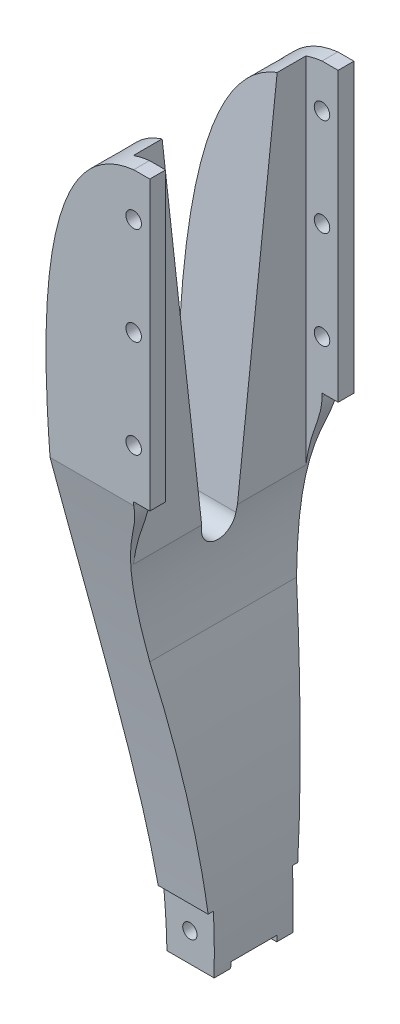
SolidWorks part; units mm, degrees
material "1060-H12"
ref_plane "Front Plane" through (0, 0, 0) normal (0, 0, 1) x (1, 0, 0)
ref_plane "Top Plane" through (0, 0, 0) normal (0, 1, 0) x (1, 0, 0)
ref_plane "Right Plane" through (0, 0, 0) normal (1, 0, 0) x (0, 0, -1)
ref_plane "Plane1" through (0, 35.6, 0) normal (0, 1, 0) x (-1, 0, 0)
sketch "Sketch1" plane through (0, 0, 0) normal (0, 0, 1) x (1, 0, 0)
  line L0 (5.6, 35.6) -> (5.6, -15)
  line L1 (-4.0881, -120.4081) -> (3.5407, -122.8051)
  spline S0 degree 3 poles (5.6, 35.6) (-12.3679, 33.5213) (-8.7824, -50.7826) (5.9542, -91.4515) (-4.0881, -120.4081) knots 0 0 0 0 0.405307 1 1 1 1
  spline S1 degree 2 poles (3.4094, -42.1161) (14.0214, -91.1985) (3.5407, -122.8051) knots 0 0 0 1 1 1
  spline S3 degree 3 poles (5.6, -15) (5.6, -17.2744) (1.6042, -25.848) (2.4158, -35.1136) (3.4094, -42.1161) knots 0 0 0 0 0.227789 0.9215 0.9215 0.9215 0.9215
extrude "Boss-Extrude2" add sketch "Sketch1" along normal blind 35.5
sketch "Sketch3" plane through (0, 0, 0) normal (1, 0, 0) x (0, 0, -1)
  line L0 (0, -14.9824) -> (29.6274, -14.9824)
  line L1 (0, -120.4081) -> (0, 35.6) construction
  line L3 (29.6274, -14.9824) -> (29.6274, -131.5725)
  line L4 (-12.75, -120.4081) -> (-22.7692, -120.4081)
  line L6 (29.6274, -131.5725) -> (-60.5471, -131.5725)
  line L7 (-35.5, 35.6) -> (-35.5, -120.4081) construction
  line L8 (-60.5471, -131.5725) -> (-60.5471, -14.9824)
  line L9 (-60.5471, -14.9824) -> (-35.5, -14.9824)
  spline S0 degree 3 poles (0, -14.9824) (-7.1912, -49.7586) (-11.4412, -85.1664) (-12.75, -120.4081) knots 0 0 0 0 1 1 1 1
  spline S1 degree 3 poles (-35.5, -14.9824) (-28.3088, -49.7586) (-24.078, -85.1664) (-22.7692, -120.4081) knots 0 0 0 0 1 1 1 1
extrude "Cut-Extrude1" cut sketch "Sketch3" against normal mid plane 35.5
sketch "Sketch4" plane through (5.6, 0, 0) normal (1, 0, 0) x (0, 0, -1)
  line L1 (-2.75, 35.6) -> (-32.75, 35.6)
  line L2 (-2.75, 35.6) -> (-2.75, -15)
  line L3 (0, -14.9824) -> (0, 35.6) construction
  line L4 (-32.75, 35.6) -> (-32.75, -15)
  line L5 (-35.4964, -15) -> (-0.0036, -15) construction
  line L8 (-32.75, -15) -> (-32.75, -32.0181)
  line L9 (-32.75, -32.0181) -> (-2.75, -32.0181)
  line L10 (-2.75, -15) -> (-2.75, -32.0181)
  dimension "D1" = 30
  dimension "D2" = 30
  dimension "D3" = 2.75
extrude "Cut-Extrude2" cut sketch "Sketch4" against normal blind 2.8
sketch "Sketch5" plane through (0, 35.6, 0) normal (0, 1, 0) x (1, 0, 0)
  line L1 (5.6, 0) -> (8.4, 0)
  line L2 (5.6, 0) -> (5.6, -2.75)
  line L3 (5.6, -2.75) -> (8.4, -2.75)
  line L4 (8.4, 0) -> (8.4, -2.75)
  line L6 (5.6, -35.5) -> (8.4, -35.5)
  line L7 (5.6, -35.5) -> (5.6, -32.75)
  line L8 (5.6, -32.75) -> (8.4, -32.75)
  line L9 (8.4, -35.5) -> (8.4, -32.75)
  dimension "D1" = 2.8
  dimension "D2" = 2.75
  dimension "D3" = 2.75
  dimension "D4" = 2.8
extrude "Boss-Extrude3" add sketch "Sketch5" against normal blind 50
sketch "Sketch6" plane through (0, 0, 0) normal (1, 0, 0) x (0, 0, -1)
  line L0 (-7.75, 34.9693) -> (-14.7818, -27.8088)
  line L1 (-2.75, 34.9693) -> (-32.75, 34.9693) construction
  line L2 (-20.7446, -27.8076) -> (-27.75, 34.9693)
  line L3 (-7.75, 34.9693) -> (-27.75, 34.9693)
  arc A0 (-20.7446, -27.8076) -> (-14.7818, -27.8088) centre (-17.7631, -27.4748) ccw
  circle A1 centre (0, 0) radius 1
extrude "Cut-Extrude3" cut sketch "Sketch6" against normal mid plane 30
ref_plane "Plane2" through (4.2977, -120.4081, 22.7692) normal (-0.2874, -0.9571, -0.0355) x (0.9578, -0.2872, -0.0107)
hole_wizard "Ø2.7 (2.7) Diameter Hole1" positions "Sketch8" profile "Sketch7" hole size "Ø2.7" standard "ISO" end condition through all
sketch "Sketch8" plane through (0, 0, 35.5) normal (0, 0, 1) x (1, 0, 0)
  line L0 (8.4, -14.4) -> (8.4, 35.6) construction
  line L1 (5.6, 35.6) -> (8.4, 35.6) construction
  point P0 (5.6, 28.1)
  point P1 (5.6, 11.1)
  point P3 (5.6, -5.9)
  dimension "D1" = 2.8
  dimension "D2" = 2.8
  dimension "D3" = 2.8
  dimension "D4" = 41.5
  dimension "D5" = 7.5
  dimension "D6" = 24.5
sketch "Sketch7" plane through (5.6, 28.1, 35.5) normal (1, 0, 0) x (0, -1, 0)
  line L0 (0, 0) -> (0, 35.5)
  line L1 (0, 35.5) -> (1.35, 35.5)
  line L2 (1.35, 35.5) -> (1.35, 0)
  line L5 (1.35, 0) -> (0, 0)
  line L11 (0, -6.35) -> (0, 107.95) construction
  dimension "Thru Hole Dia." = 2.7
  dimension "Thru Hole Depth" = 35.5
hole_wizard "M3 Tapped Hole1" positions "Sketch10" profile "Sketch11" tap size "M3" standard "ISO" end condition through all
sketch "Sketch10" plane through (0, 0, 35.5) normal (0, 0, 1) x (1, 0, 0)
  point P0 (4.5, -85)
sketch "Sketch11" plane through (4.5, -85, 35.5) normal (1, 0, 0) x (0, -1, 0)
  line L0 (0, 0) -> (0, 42.9602)
  line L1 (0, 42.9602) -> (1.25, 42.9602)
  line L2 (1.25, 42.9602) -> (1.25, 0)
  line L5 (1.25, 0) -> (0, 0)
  line L11 (0, -6.35) -> (0, 107.95) construction
  dimension "Thru Tap Drill Dia." = 2.5
  dimension "Thru Tap Drill Depth" = 42.9602
cosmetic thread "Hole Thread1" parameters "D2"=3
sketch "Sketch12" plane through (0, 0, 0) normal (1, 0, 0) x (0, 0, -1)
  line L0 (-9.3959, -80) -> (-10.8927, -80)
  line L1 (-10.8927, -80) -> (-10.8927, -90)
  line L2 (-10.8927, -90) -> (-9.3959, -90)
  line L3 (-9.3959, -90) -> (-9.3959, -80)
  line L4 (-24.6227, -80) -> (-24.6227, -90)
  line L5 (-24.6227, -90) -> (-26.1946, -90)
  line L6 (-26.1946, -90) -> (-26.1946, -80)
  line L7 (-26.1946, -80) -> (-24.6227, -80)
  spline S0 degree 3 poles (0, -14.9824) (-7.1912, -49.7586) (-11.4412, -85.1664) (-12.75, -120.4081) knots 0 0 0 0 1 1 1 1 construction
  spline S1 degree 3 poles (-22.7692, -120.4081) (-24.078, -85.1664) (-28.3088, -49.7586) (-35.5, -14.9824) knots 0 0 0 0 1 1 1 1 construction
  dimension "D1" = 90
  dimension "D2" = 10
extrude "Cut-Extrude4" cut sketch "Sketch12" along normal through all and the other way through all
sketch "Sketch14" plane through (0, 0, 10.8927) normal (0, 0, -1) x (-1, 0, 0)
  line L0 (-8.7203, -90) -> (6.2727, -90)
  line L1 (6.2727, -90) -> (6.2727, -124.0936)
  line L2 (6.2727, -124.0936) -> (-10.5411, -124.0936)
  line L3 (-10.5411, -124.0936) -> (-10.5411, -90)
  line L4 (-10.5411, -90) -> (-8.7203, -90)
extrude "Cut-Extrude5" cut sketch "Sketch14" against normal blind 20
sketch "Sketch15" plane through (0, -90, 0) normal (0, -1, 0) x (-1, 0, 0)
  line L2 (-8.7203, -10.8927) -> (-0.5063, -10.8927) construction
  line L5 (-5.2203, -13.7427) -> (-8.7203, -13.7427)
  line L6 (-8.7203, -24.6227) -> (-8.7203, -10.8927) construction
  line L7 (-5.2203, -21.7427) -> (-9.6234, -21.7427)
  line L8 (-9.6234, -21.7427) -> (-9.6234, -13.7427)
  line L9 (-9.6234, -13.7427) -> (-8.7203, -13.7427)
  arc A0 (-5.2203, -21.7427) -> (-5.2203, -13.7427) centre (-5.2203, -17.7427) ccw
  dimension "D1" = 8
  dimension "D2" = 6.85
  dimension "D3" = 3.5
extrude "Cut-Extrude6" cut sketch "Sketch15" against normal blind 1
sketch "Sketch16" plane through (0, 0, 35.5) normal (0, 0, 1) x (1, 0, 0)
  line L0 (20.6, 23.6) -> (5.2203, -126.5) construction
